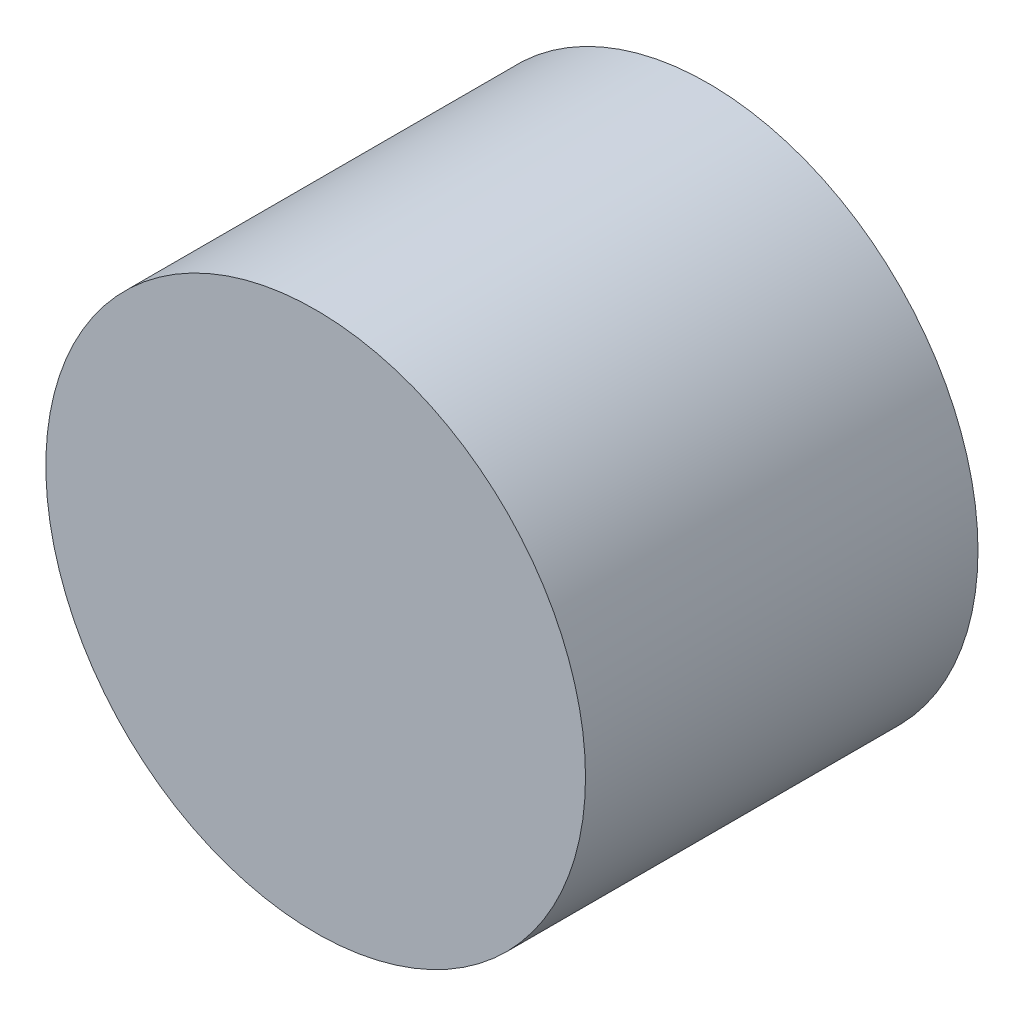
SolidWorks part; units mm, degrees
ref_plane "前视基准面" through (0, 0, 0) normal (0, 0, 1) x (1, 0, 0)
ref_plane "上视基准面" through (0, 0, 0) normal (0, 1, 0) x (1, 0, 0)
ref_plane "右视基准面" through (0, 0, 0) normal (1, 0, 0) x (0, 0, -1)
sketch "草图1" plane through (0, 0, 0) normal (0, 0, 1) x (1, 0, 0)
  circle A0 centre (0, 0) radius 5.5
  dimension "D1" = 11
extrude "凸台-拉伸1" add sketch "草图1" along normal blind 8
